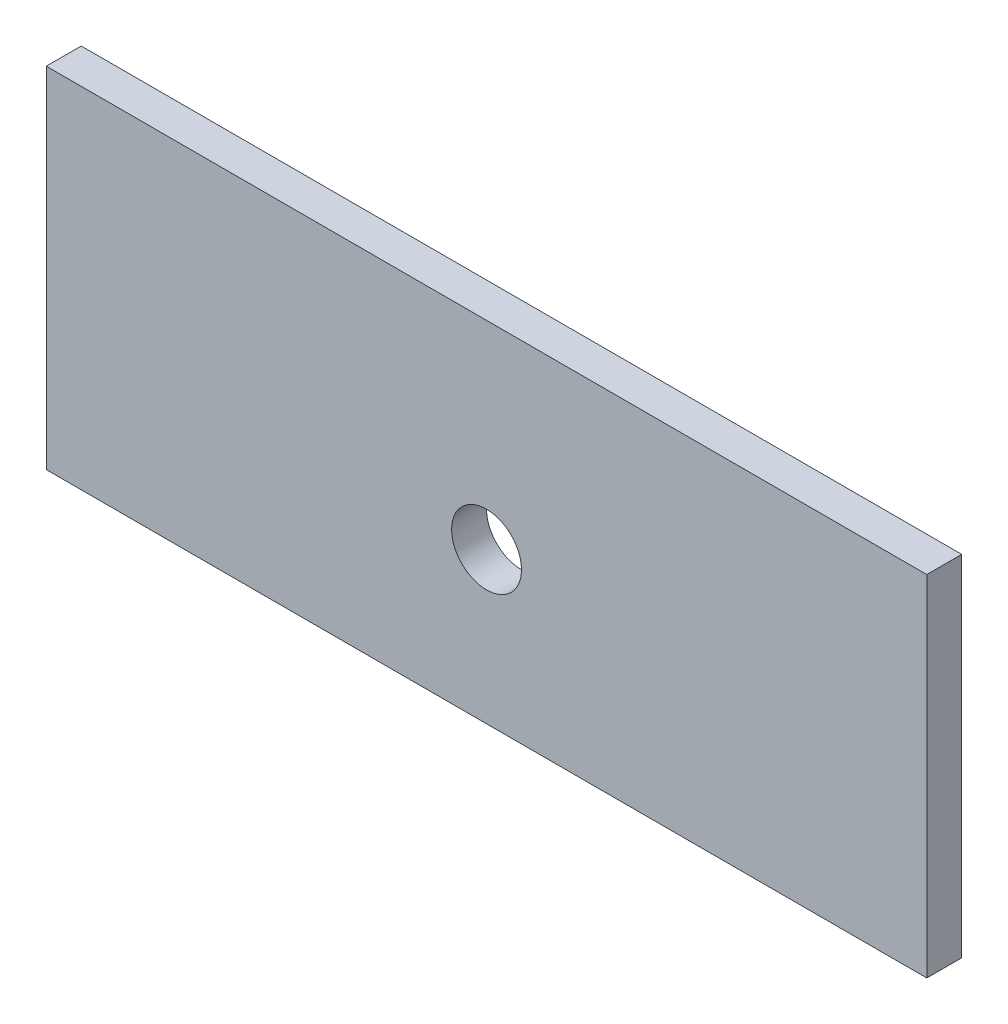
SolidWorks part; units mm, degrees
ref_plane "Front Plane" through (0, 0, 0) normal (0, 0, 1) x (1, 0, 0)
ref_plane "Top Plane" through (0, 0, 0) normal (0, 1, 0) x (1, 0, 0)
ref_plane "Right Plane" through (0, 0, 0) normal (1, 0, 0) x (0, 0, -1)
sketch "Sketch4" plane through (0, 0, 0) normal (0, 0, 1) x (1, 0, 0)
  line L0 (-12.9323, 21.992) -> (67.0777, 21.992)
  line L1 (67.0777, 21.992) -> (67.0777, -9.758)
  line L2 (67.0777, -9.758) -> (-12.9323, -9.758)
  line L3 (-12.9323, -9.758) -> (-12.9323, 21.992)
  dimension "D1" = 31.75
  dimension "D2" = 80.01
extrude "Boss-Extrude1" add sketch "Sketch4" along normal blind 3.175 contours L3 L0 L1 L2
sketch "Sketch5" plane through (0, 0, 0) normal (0, 0, -1) x (-1, 0, 0)
  line L2 (-67.0777, 21.992) -> (-67.0777, -9.758) construction
  line L3 (-67.0777, -9.758) -> (12.9323, -9.758) construction
  circle A0 centre (-27.0727, 3.958) radius 3.175
  point P4 (0, 0)
  dimension "D1" = 6.35
  dimension "D2" = 13.716
  dimension "D3" = 40.005
extrude "Cut-Extrude1" cut sketch "Sketch5" against normal blind 12.7
